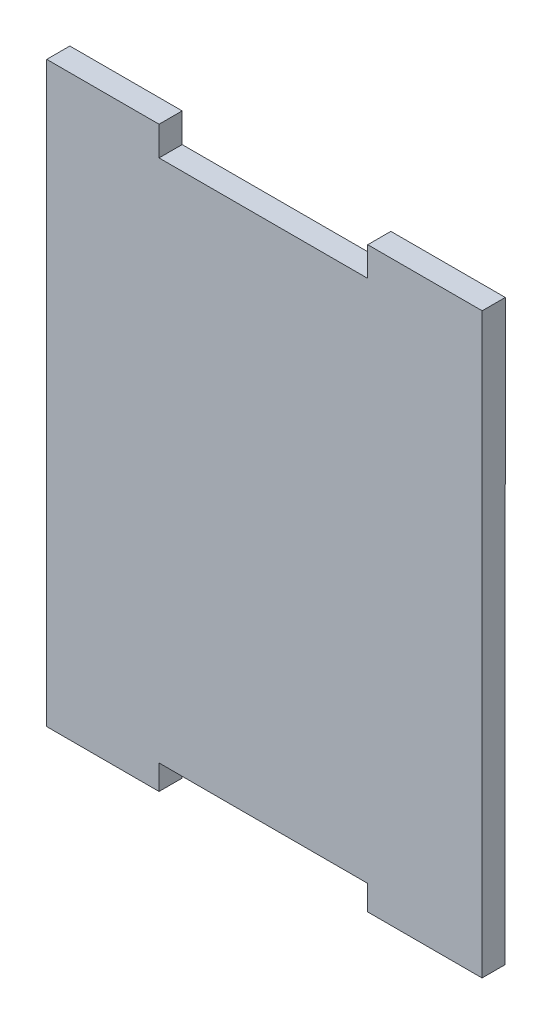
SolidWorks part; units mm, degrees
ref_plane "Front Plane" through (0, 0, 0) normal (0, 0, 1) x (1, 0, 0)
ref_plane "Top Plane" through (0, 0, 0) normal (0, 1, 0) x (1, 0, 0)
ref_plane "Right Plane" through (0, 0, 0) normal (1, 0, 0) x (0, 0, -1)
sketch "Sketch1" plane through (0, 0, 0) normal (0, 0, 1) x (1, 0, 0)
  line L0 (300.8707, 171.6819) -> (327.9562, 171.6819)
  line L1 (327.9562, 171.6819) -> (327.9566, 175.4719)
  line L2 (327.9566, 175.4719) -> (342.806, 175.4704)
  line L6 (342.7931, 100.4704) -> (327.9436, 100.4719)
  line L7 (327.9436, 100.4719) -> (327.944, 103.6819)
  line L8 (327.944, 103.6819) -> (300.8724, 103.6819)
  line L9 (300.8724, 103.6819) -> (300.8716, 100.4719)
  line L10 (300.8716, 100.4719) -> (286.2931, 100.4732)
  line L14 (286.2931, 175.4732) -> (300.8716, 175.4719)
  line L15 (300.8716, 175.4719) -> (300.8707, 171.6819)
  line L16 (286.2931, 175.4732) -> (286.2931, 100.4732)
  line L17 (342.806, 175.4704) -> (342.7931, 100.4704)
  dimension "D1" = 75
  dimension "D2" = 68
  dimension "D3" = 56.5
  dimension "D4" = 14.5786
  dimension "D5" = 27.0716
extrude "Boss-Extrude1" add sketch "Sketch1" along normal blind 3 contours L14 L15 L0 L1 L2 L17 L6 L7 L8 L9 L10 L16
